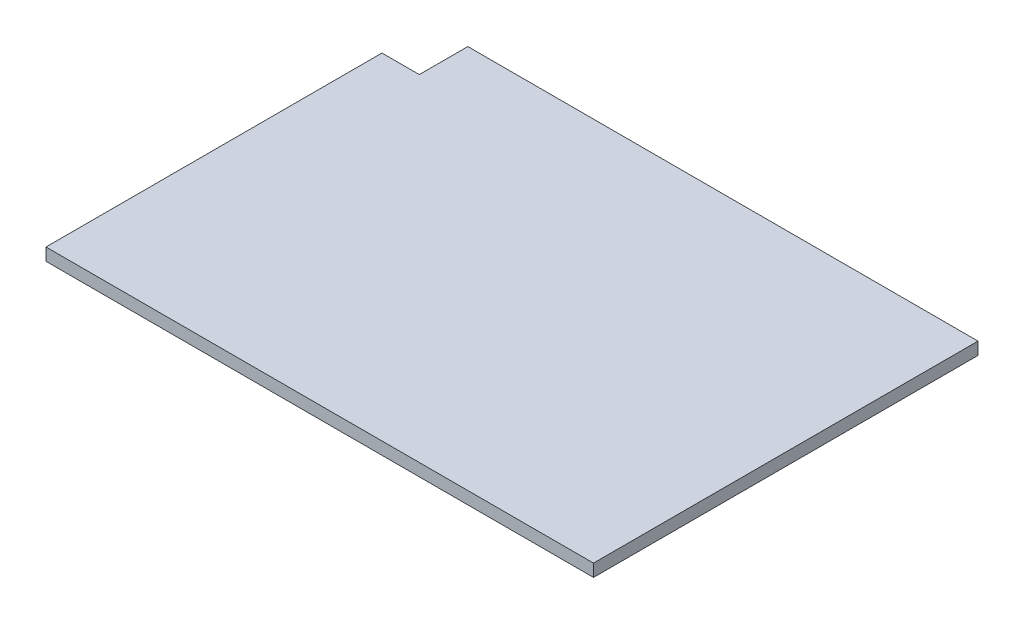
SolidWorks part; units mm, degrees
ref_plane "Front Plane" through (0, 0, 0) normal (0, 0, 1) x (1, 0, 0)
ref_plane "Top Plane" through (0, 0, 0) normal (0, 1, 0) x (1, 0, 0)
ref_plane "Right Plane" through (0, 0, 0) normal (1, 0, 0) x (0, 0, -1)
sketch "Sketch1" plane through (0, 0, 0) normal (0, 1, 0) x (1, 0, 0)
  line L1 (0, 0) -> (440, 0)
  line L2 (0, 0) -> (0, 270)
  line L3 (30, 309) -> (440, 309)
  line L4 (440, 0) -> (440, 309)
  line L7 (0, 270) -> (30, 270)
  line L8 (30, 309) -> (30, 270)
  dimension "D1" = 440
  dimension "D2" = 309
  dimension "D3" = 39
  dimension "D4" = 30
extrude "Boss-Extrude1" add sketch "Sketch1" along normal blind 10
